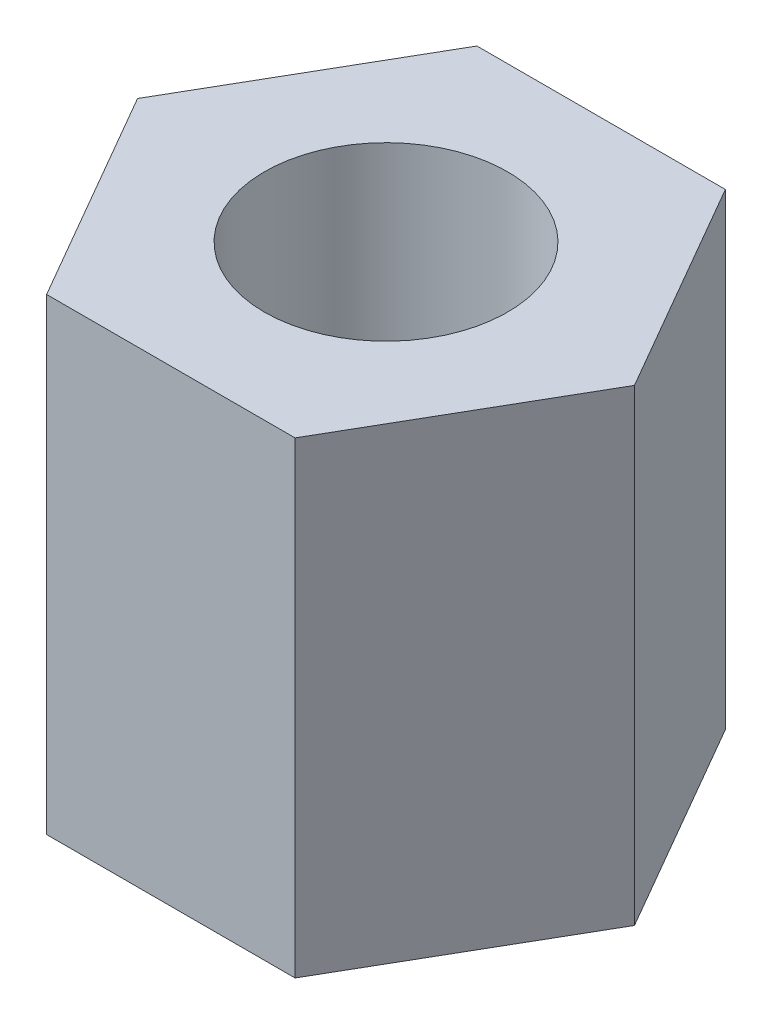
SolidWorks part; units mm, degrees
ref_plane "Front Plane" through (0, 0, 0) normal (0, 0, 1) x (1, 0, 0)
ref_plane "Top Plane" through (0, 0, 0) normal (0, 1, 0) x (1, 0, 0)
ref_plane "Right Plane" through (0, 0, 0) normal (1, 0, 0) x (0, 0, -1)
sketch "Croquis1" plane through (0, 0, 0) normal (0, 1, 0) x (1, 0, 0)
  line L1 (1.3279, -2.3) -> (2.6558, 0)
  line L2 (2.6558, 0) -> (1.3279, 2.3)
  line L3 (1.3279, 2.3) -> (-1.3279, 2.3)
  line L4 (-1.3279, 2.3) -> (-2.6558, 0)
  line L5 (-2.6558, 0) -> (-1.3279, -2.3)
  line L6 (-1.3279, -2.3) -> (1.3279, -2.3)
  circle A0 centre (0, 0) radius 2.3 construction
  circle A1 centre (0, 0) radius 1.3
  dimension "D2" = 2.6
  dimension "D1" = 4.6
extrude "Saliente-Extruir1" add sketch "Croquis1" along normal blind 5
